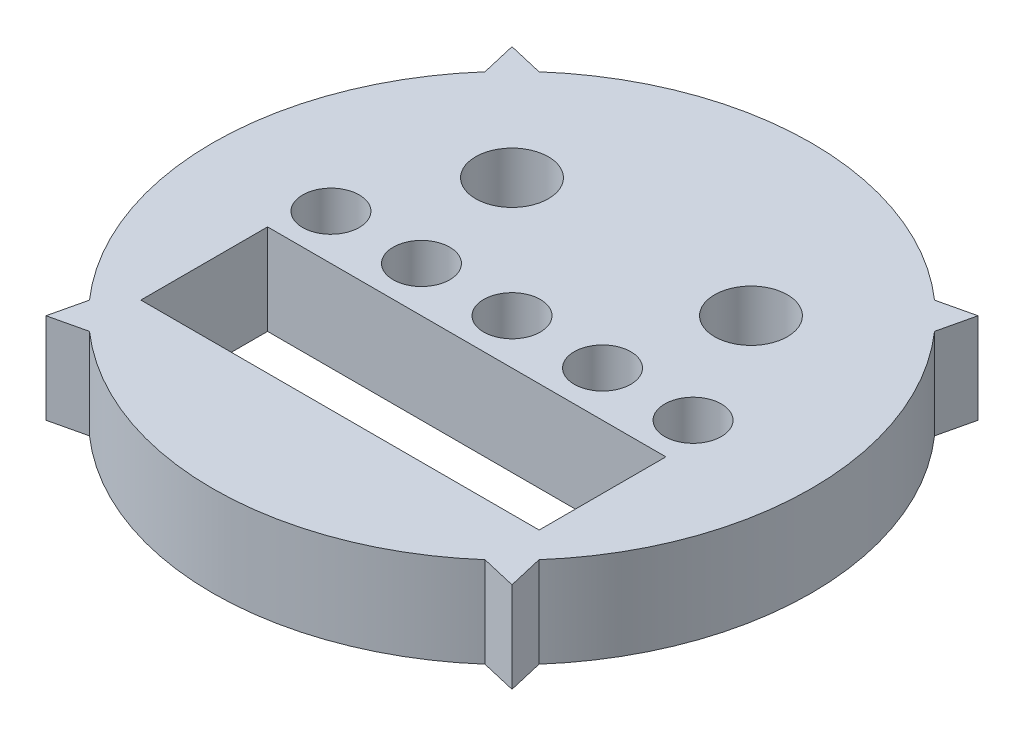
SolidWorks part; units mm, degrees
ref_plane "Front Plane" through (0, 0, 0) normal (0, 0, 1) x (1, 0, 0)
ref_plane "Top Plane" through (0, 0, 0) normal (0, 1, 0) x (1, 0, 0)
ref_plane "Right Plane" through (0, 0, 0) normal (1, 0, 0) x (0, 0, -1)
sketch "Sketch1" plane through (0, 0, 0) normal (0, 1, 0) x (1, 0, 0)
  line L0 (13.8701, 15.7677) -> (16.3439, 16.3439)
  line L1 (16.3439, 16.3439) -> (15.7677, 13.8701)
  line L2 (15.7677, -13.8701) -> (16.3439, -16.3439)
  line L3 (16.3439, -16.3439) -> (13.8701, -15.7677)
  line L4 (-13.8701, -15.7677) -> (-16.3439, -16.3439)
  line L5 (-16.3439, -16.3439) -> (-15.7677, -13.8701)
  line L6 (-15.7677, 13.8701) -> (-16.3439, 16.3439)
  line L7 (-16.3439, 16.3439) -> (-13.8701, 15.7677)
  line L8 (16.3439, 16.3439) -> (0, 0) construction
  line L9 (0, 0) -> (21, 0) construction
  line L10 (-20.7586, -3.175) -> (20.7586, -3.175) construction
  line L12 (-13.97, -3.175) -> (13.97, -3.175)
  line L13 (-13.97, -3.175) -> (-13.97, -12.065)
  line L14 (-13.97, -12.065) -> (13.97, -12.065)
  line L15 (13.97, -3.175) -> (13.97, -12.065)
  arc A0 (13.8701, 15.7677) -> (-13.8701, 15.7677) centre (0, 0) ccw
  arc A1 (15.7677, -13.8701) -> (15.7677, 13.8701) centre (0, 0) ccw
  arc A2 (-13.8701, -15.7677) -> (13.8701, -15.7677) centre (0, 0) ccw
  arc A3 (-15.7677, 13.8701) -> (-15.7677, -13.8701) centre (0, 0) ccw
  circle A4 centre (-12.7, 0) radius 1.9844
  circle A5 centre (-6.35, 0) radius 1.9844
  circle A6 centre (0, 0) radius 1.9844
  circle A7 centre (-8.382, 8.382) radius 2.5527
  circle A8 centre (8.382, 8.382) radius 2.5527
  circle A9 centre (6.35, 0) radius 1.9844
  circle A10 centre (12.7, 0) radius 1.9844
  point P18 (0, 0)
  point P28 (0, -12.065)
  dimension "D1" = 42
  dimension "D7" = 3.9688
  dimension "D14" = 5.1054
  dimension "D2" = 2.54
  dimension "D3" = 2.54
  dimension "D5" = 23.1137
  dimension "D6" = 45
  dimension "D8" = 12.7
  dimension "D10" = 3.175
  dimension "D11" = 8.89
  dimension "D12" = 27.94
  dimension "D13" = 6.35
  dimension "D15" = 8.382
  dimension "D16" = 8.382
  dimension "D9" = 5
  dimension "D17" = 2
  dimension "D4" = 4
extrude "Boss-Extrude1" add sketch "Sketch1" along normal blind 6.35
